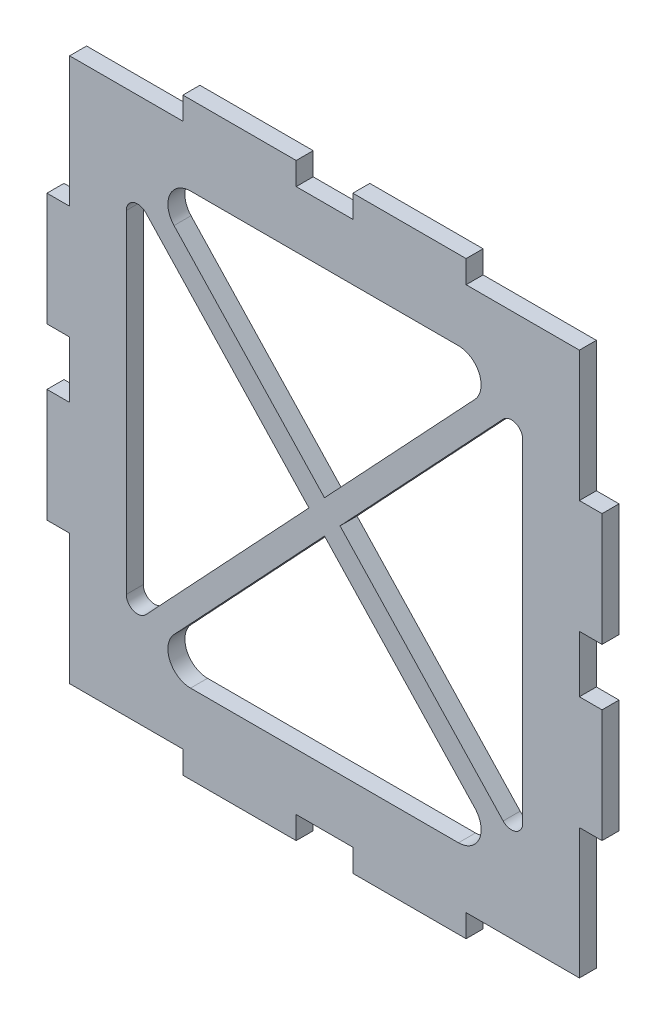
SolidWorks part; units mm, degrees
ref_plane "前视基准面" through (0, 0, 0) normal (0, 0, 1) x (1, 0, 0)
ref_plane "上视基准面" through (0, 0, 0) normal (0, 1, 0) x (1, 0, 0)
ref_plane "右视基准面" through (0, 0, 0) normal (1, 0, 0) x (0, 0, -1)
other "Configuration Table"
sketch "草图1" plane through (0, 0, 0) normal (0, 0, 1) x (1, 0, 0)
  line L0 (2017.284, 1091.3739) -> (2017.284, 1092.1239)
  line L1 (2017.284, 1092.1239) -> (2017.284, 1092.8739)
  line L2 (2017.284, 1092.1239) -> (2017.284, 1092.8739)
  line L3 (2017.284, 1092.8739) -> (2017.284, 1092.1239)
  line L4 (1997.284, 1091.3739) -> (2007.284, 1091.3739)
  line L5 (2032.284, 1091.3739) -> (2042.284, 1091.3739)
  line L6 (2017.284, 1091.3739) -> (2022.284, 1091.3739)
  line L7 (2007.284, 1091.3739) -> (2007.284, 1093.3739)
  line L8 (2007.284, 1093.3739) -> (2017.284, 1093.3739)
  line L9 (2017.284, 1093.3739) -> (2017.284, 1092.8739)
  line L10 (2022.284, 1093.3739) -> (2032.284, 1093.3739)
  line L11 (2022.284, 1091.3739) -> (2022.284, 1093.3739)
  line L12 (2032.284, 1093.3739) -> (2032.284, 1091.3739)
  line L13 (2042.284, 1043.3739) -> (2042.284, 1054.8739)
  line L14 (2042.284, 1064.8739) -> (2042.284, 1069.8739)
  line L15 (2042.284, 1079.8739) -> (2042.284, 1091.3739)
  line L16 (2042.284, 1079.8739) -> (2044.284, 1079.8739)
  line L17 (2044.284, 1079.8739) -> (2044.284, 1069.8739)
  line L18 (2042.284, 1069.8739) -> (2044.284, 1069.8739)
  line L19 (2042.284, 1064.8739) -> (2044.284, 1064.8739)
  line L20 (2044.284, 1064.8739) -> (2044.284, 1054.8739)
  line L21 (2044.284, 1054.8739) -> (2042.284, 1054.8739)
  line L22 (2017.284, 1091.3739) -> (2019.784, 1091.3739)
  line L23 (1997.284, 1043.3739) -> (1997.284, 1054.8739)
  line L24 (1997.284, 1064.8739) -> (1997.284, 1069.8739)
  line L25 (1997.284, 1079.8739) -> (1997.284, 1091.3739)
  line L26 (1997.284, 1079.8739) -> (1995.284, 1079.8739)
  line L27 (1995.284, 1079.8739) -> (1995.284, 1069.8739)
  line L28 (1997.284, 1069.8739) -> (1995.284, 1069.8739)
  line L29 (1997.284, 1064.8739) -> (1995.284, 1064.8739)
  line L30 (1995.284, 1064.8739) -> (1995.284, 1054.8739)
  line L31 (1995.284, 1054.8739) -> (1997.284, 1054.8739)
  line L32 (1997.284, 1069.8739) -> (1997.284, 1067.3739)
  line L33 (2017.284, 1043.3739) -> (2017.284, 1042.6239)
  line L34 (2017.284, 1042.6239) -> (2017.284, 1041.8739)
  line L35 (2017.284, 1042.6239) -> (2017.284, 1041.8739)
  line L36 (2017.284, 1041.8739) -> (2017.284, 1042.6239)
  line L37 (1997.284, 1043.3739) -> (2007.284, 1043.3739)
  line L38 (2032.284, 1043.3739) -> (2042.284, 1043.3739)
  line L39 (2017.284, 1043.3739) -> (2022.284, 1043.3739)
  line L40 (2007.284, 1043.3739) -> (2007.284, 1041.3739)
  line L41 (2007.284, 1041.3739) -> (2017.284, 1041.3739)
  line L42 (2017.284, 1041.3739) -> (2017.284, 1041.8739)
  line L43 (2022.284, 1041.3739) -> (2032.284, 1041.3739)
  line L44 (2022.284, 1043.3739) -> (2022.284, 1041.3739)
  line L45 (2032.284, 1041.3739) -> (2032.284, 1043.3739)
  line L46 (2017.284, 1043.3739) -> (2019.784, 1043.3739)
  line L47 (2037.284, 1082.0758) -> (2037.284, 1052.6601)
  line L48 (2006.4996, 1083.006) -> (2019.784, 1068.836)
  line L49 (2004.0135, 1082.7336) -> (2018.4133, 1067.3739)
  line L50 (2019.784, 1065.9118) -> (2033.1128, 1051.6944)
  line L51 (2003.9907, 1051.9898) -> (2018.4133, 1067.3739)
  line L52 (2019.784, 1068.836) -> (2033.0984, 1083.0381)
  line L53 (2021.1547, 1067.3739) -> (2035.5548, 1082.7332)
  line L54 (2007.9587, 1086.3739) -> (2031.6097, 1086.3736)
  line L55 (2002.284, 1082.0497) -> (2002.2844, 1052.6976)
  line L56 (2019.784, 1065.9118) -> (2006.5, 1051.7414)
  line L57 (2035.5552, 1052.015) -> (2021.1547, 1067.3739)
  line L58 (2007.9592, 1048.3736) -> (2031.6103, 1048.3745)
  arc A0 (2004.0135, 1082.7336) -> (2002.284, 1082.0497) centre (2003.284, 1082.0497) ccw
  arc A1 (2007.9587, 1086.3739) -> (2006.4996, 1083.006) centre (2007.9587, 1084.3739) ccw
  arc A2 (2037.2843, 1082.0493) -> (2035.5548, 1082.7332) centre (2036.2843, 1082.0493) ccw
  arc A3 (2033.0687, 1083.0057) -> (2031.6097, 1086.3736) centre (2031.6097, 1084.3736) ccw
  arc A4 (2002.2844, 1052.6976) -> (2004.0139, 1052.0138) centre (2003.2844, 1052.6977) ccw
  arc A5 (2006.5, 1051.7414) -> (2007.9592, 1048.3736) centre (2007.9591, 1050.3736) ccw
  arc A6 (2035.5552, 1052.015) -> (2037.2847, 1052.699) centre (2036.2847, 1052.699) ccw
  arc A7 (2031.6103, 1048.3745) -> (2033.0692, 1051.7425) centre (2031.6102, 1050.3745) ccw
extrude "凸台-拉伸1" add sketch "草图1" along normal blind 1.5
